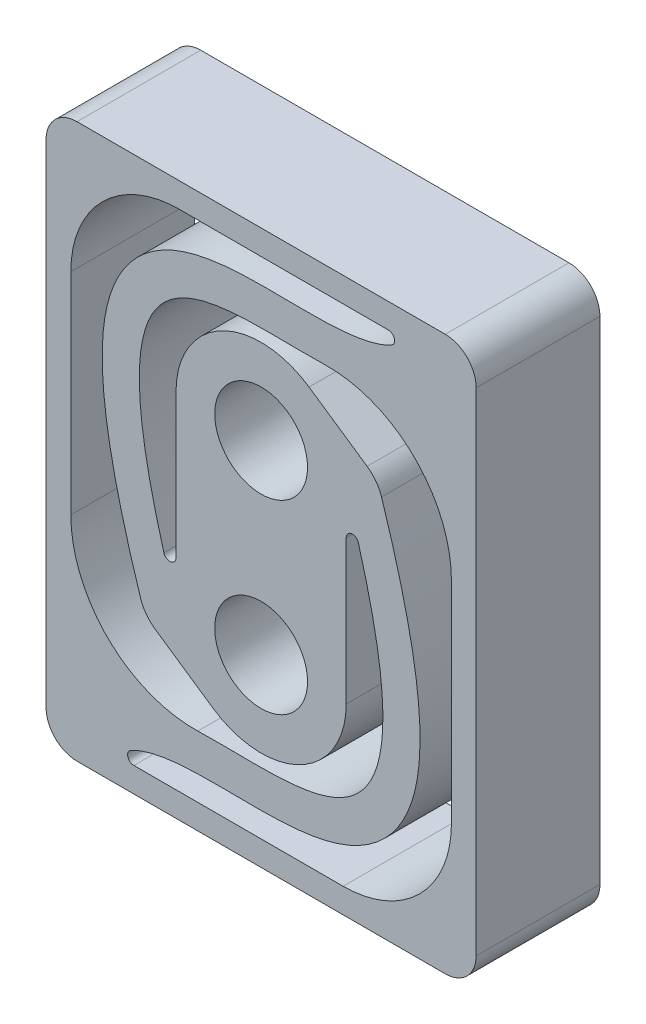
SolidWorks part; units mm, degrees
ref_plane "Front Plane" through (0, 0, 0) normal (0, 0, 1) x (1, 0, 0)
ref_plane "Top Plane" through (0, 0, 0) normal (0, 1, 0) x (1, 0, 0)
ref_plane "Right Plane" through (0, 0, 0) normal (1, 0, 0) x (0, 0, -1)
sketch "Sketch1" plane through (0, 0, 0) normal (0, 0, 1) x (1, 0, 0)
  line L0 (0, 3) -> (0, -3) construction
  line L1 (0, 3) -> (0, -3) construction
  line L2 (2.75, 3) -> (2.75, -3)
  line L3 (-2.75, 3) -> (-2.75, -3)
  circle A0 centre (0, 3) radius 1.5
  circle A1 centre (0, -3) radius 1.5
  arc A2 (2.75, 3) -> (-2.75, 3) centre (0, 3) ccw
  arc A3 (-2.75, -3) -> (2.75, -3) centre (0, -3) ccw
  point P2 (0, 0)
  point P7 (0, 0)
  dimension "D2" = 3
  dimension "D1" = 6
  dimension "D3" = 5.5
extrude "Boss-Extrude1" add sketch "Sketch1" along normal blind 4
sketch "Sketch3" plane through (0, 0, 0) normal (0, 0, 1) x (1, 0, 0)
  line L0 (-2.65, 8.15) -> (6.15, 8.15) construction
  line L1 (-6.15, 4.65) -> (-6.15, -8.15) construction
  line L4 (-6.15, -8.15) -> (2.65, -8.15) construction
  line L9 (-6.15, 8.15) -> (6.15, -8.15) construction
  line L10 (-6.15, -8.15) -> (6.15, 8.15) construction
  line L12 (-6.95, 8.95) -> (-6.95, -8.95)
  line L13 (-6.95, -8.95) -> (6.95, -8.95)
  line L14 (6.95, 8.95) -> (6.95, -8.95)
  line L15 (-6.95, 8.95) -> (6.95, 8.95)
  line L32 (6.15, 8.15) -> (6.15, -4.65) construction
  line L34 (-1.55, -5.2716) -> (-3.4264, -3.9912)
  line L36 (-0.85, -6.15) -> (6.15, -6.15) construction
  line L37 (0.85, 6.15) -> (-6.15, 6.15) construction
  line L39 (0.85, 6.15) -> (0.85, 8.15) construction
  line L40 (4.8361, 6.75) -> (4.8361, 8.15) construction
  line L41 (4.8361, 6.75) -> (6.15, 6.75) construction
  line L42 (-0.85, -6.15) -> (-0.85, -8.15) construction
  line L43 (-4.8361, -6.75) -> (-4.8361, -8.15) construction
  line L44 (-4.8361, -6.75) -> (-6.15, -6.75) construction
  line L45 (1.55, 5.2716) -> (3.4264, 3.9912)
  line L46 (2.75, -3) -> (2.75, 3) construction
  line L47 (-2.75, -1.6573) -> (-2.75, -3)
  line L48 (-6.15, 4.65) -> (-6.15, -2.1542)
  line L49 (6.15, 2.1542) -> (6.15, -4.65)
  line L50 (-2.65, 8.15) -> (4.1129, 8.15)
  line L51 (-4.1129, -8.15) -> (2.65, -8.15)
  line L52 (-2.75, 3) -> (-2.75, -3) construction
  line L53 (2.75, 3) -> (2.75, 1.6573)
  arc A0 (-3.8923, -3.3675) -> (-3.4264, -3.9912) centre (-2.75, -3) ccw
  arc A1 (3.8923, 3.3675) -> (3.4264, 3.9912) centre (2.75, 3) ccw
  arc A2 (2.65, -8.15) -> (6.15, -4.65) centre (2.65, -4.65) ccw
  arc A3 (-6.15, 4.65) -> (-2.65, 8.15) centre (-2.65, 4.65) cw
  arc A5 (-2.044, -6.1528) -> (-6.15, -2.1542) centre (-2.15, -2.1542) cw
  arc A6 (2.044, 6.1528) -> (6.15, 2.1542) centre (2.15, 2.1542) cw
  arc A7 (-4.2072, -7.7736) -> (-4.1129, -8.15) centre (-4.1129, -7.95) ccw
  arc A8 (4.1129, 8.15) -> (4.2072, 7.7736) centre (4.1129, 7.95) cw
  arc A9 (-2.75, -3) -> (2.75, -3) centre (0, -3) ccw construction
  arc A10 (2.75, 3) -> (-2.75, 3) centre (0, 3) ccw construction
  arc A11 (1.55, 5.2716) -> (2.75, 3) centre (0, 3) cw
  arc A12 (-1.55, -5.2716) -> (-2.75, -3) centre (0, -3) cw
  arc A13 (-3.1423, -1.7123) -> (-2.75, -1.6573) centre (-2.95, -1.6573) ccw
  arc A14 (3.1423, 1.7123) -> (2.75, 1.6573) centre (2.95, 1.6573) ccw
  spline S0 degree 3 poles (-2.75, -3) (-7.5138, 11.8061) (3.4324, 2.7424) (6.15, 8.15) knots 0 0 0 0 1 1 1 1
  spline S1 degree 1 poles (-3.8923, -3.3675) (5.0778, 8.6888) knots 0 0 1 1 construction
  spline S2 degree 3 poles (-3.8923, -3.3675) (-3.9667, -3.1364) (-4.1146, -2.6643) (-4.3736, -1.7851) (-4.6454, -0.7564) (-4.8874, 0.3596) (-5.1041, 1.7087) (-5.1815, 3.1585) (-4.9628, 4.6147) (-4.3658, 5.8377) (-3.4034, 6.6941) (-2.3159, 7.1342) (-0.8676, 7.3754) (0.9237, 7.3441) (2.5736, 7.3404) (3.5584, 7.5116) (4.0338, 7.6788) (4.3149, 7.8294) (4.5039, 7.9613) (4.6413, 8.0813) (4.7706, 8.217) (4.9133, 8.3965) (5.0234, 8.5806) (5.0778, 8.6888) knots 0 0 0 0 0.015625 0.03125 0.0625 0.09375 0.125 0.1875 0.25 0.3125 0.375 0.4375 0.5 0.625 0.75 0.8125 0.857944 0.889194 0.910607 0.93202 0.947645 0.96875 1 1 1 1 only from (-3.8923, -3.3675) to (4.7061, 8.15)
  spline S3 degree 3 poles (2.75, 3) (7.5138, -11.8061) (-3.4324, -2.7424) (-6.15, -8.15) knots 0 0 0 0 1 1 1 1
  spline S4 degree 1 poles (3.8923, 3.3675) (-5.0778, -8.6888) knots 0 0 1 1 construction
  spline S5 degree 3 poles (3.8923, 3.3675) (3.9667, 3.1364) (4.1146, 2.6643) (4.3736, 1.7851) (4.6454, 0.7564) (4.8874, -0.3596) (5.1041, -1.7087) (5.1815, -3.1585) (4.9628, -4.6147) (4.3658, -5.8377) (3.4034, -6.6941) (2.3159, -7.1342) (0.8676, -7.3754) (-0.9237, -7.3441) (-2.5736, -7.3404) (-3.5584, -7.5116) (-4.0338, -7.6788) (-4.3149, -7.8294) (-4.5039, -7.9613) (-4.6413, -8.0813) (-4.7706, -8.217) (-4.9133, -8.3965) (-5.0234, -8.5806) (-5.0778, -8.6888) knots 0 0 0 0 0.015625 0.03125 0.0625 0.09375 0.125 0.1875 0.25 0.3125 0.375 0.4375 0.5 0.625 0.75 0.8125 0.857944 0.889194 0.910607 0.93202 0.947645 0.96875 1 1 1 1 only from (3.8923, 3.3675) to (-4.7061, -8.15)
  point P3 (0, 0)
  dimension "D3" = 12.3
  dimension "D4" = 16.3
  dimension "D5" = 0.8
  dimension "D6" = 0.8
  dimension "D7" = 1.2
  dimension "D13" = 3.5
  dimension "D14" = 4
  dimension "D15" = 0.2
  dimension "D16" = 0.2
  dimension "D1" = 17.9
  dimension "D2" = 13.9
  dimension "D8" = 1.3139
  dimension "D9" = 1.4
  dimension "D10" = 7
  dimension "D11" = 2
  dimension "D12" = 1.2
extrude "Boss-Extrude2" add sketch "Sketch3" along normal blind 4
fillet "Fillet1" radius 1 4 edges at (-6.95, 8.95, 2) (-6.95, -8.95, 2) (6.95, -8.95, 2) (6.95, 8.95, 2)
